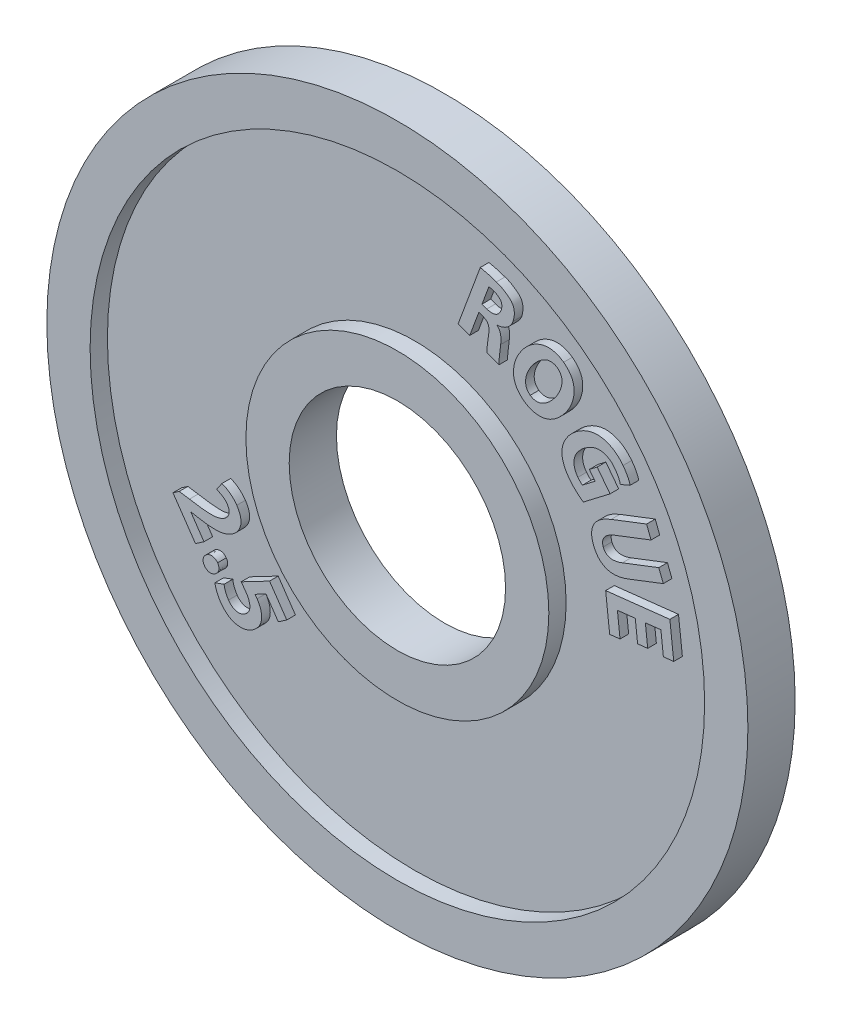
SolidWorks part; units mm, degrees
ref_plane "Front Plane" through (0, 0, 0) normal (0, 0, 1) x (1, 0, 0)
ref_plane "Top Plane" through (0, 0, 0) normal (0, 1, 0) x (1, 0, 0)
ref_plane "Right Plane" through (0, 0, 0) normal (1, 0, 0) x (0, 0, -1)
sketch "Sketch1" plane through (0, 0, 0) normal (0, 0, 1) x (1, 0, 0)
  circle A0 centre (0, 0) radius 81
  circle A1 centre (0, 0) radius 25
  dimension "D1" = 162
  dimension "D2" = 50
extrude "Boss-Extrude1" add sketch "Sketch1" along normal blind 5.461 and the other way blind 5.461
sketch "Sketch2" plane through (0, 0, 5.461) normal (0, 0, 1) x (1, 0, 0)
  circle A0 centre (0, 0) radius 35
  circle A1 centre (0, 0) radius 71
  circle A2 centre (0, 0) radius 81 construction
  circle A3 centre (0, 0) radius 25 construction
  dimension "D1" = 10
  dimension "D2" = 35
extrude "Cut-Extrude1" cut sketch "Sketch2" against normal blind 4.0005
mirror "Mirror1" about plane through (0, 0, 0) normal (0, 0, 1) of "Cut-Extrude1"
sketch "Sketch3" plane through (0, 0, 1.4605) normal (0, 0, 1) x (1, 0, 0)
  text T0 "ROGUE" font "Adobe Gothic Std B" height in points 48
extrude "Boss-Extrude2" add sketch "Sketch3" along normal blind 2
sketch "Sketch4" plane through (0, 0, 1.4605) normal (0, 0, 1) x (1, 0, 0)
  text T0 "2.5" font "Adobe Gothic Std B" height in points 48
extrude "Boss-Extrude3" add sketch "Sketch4" along normal blind 2
